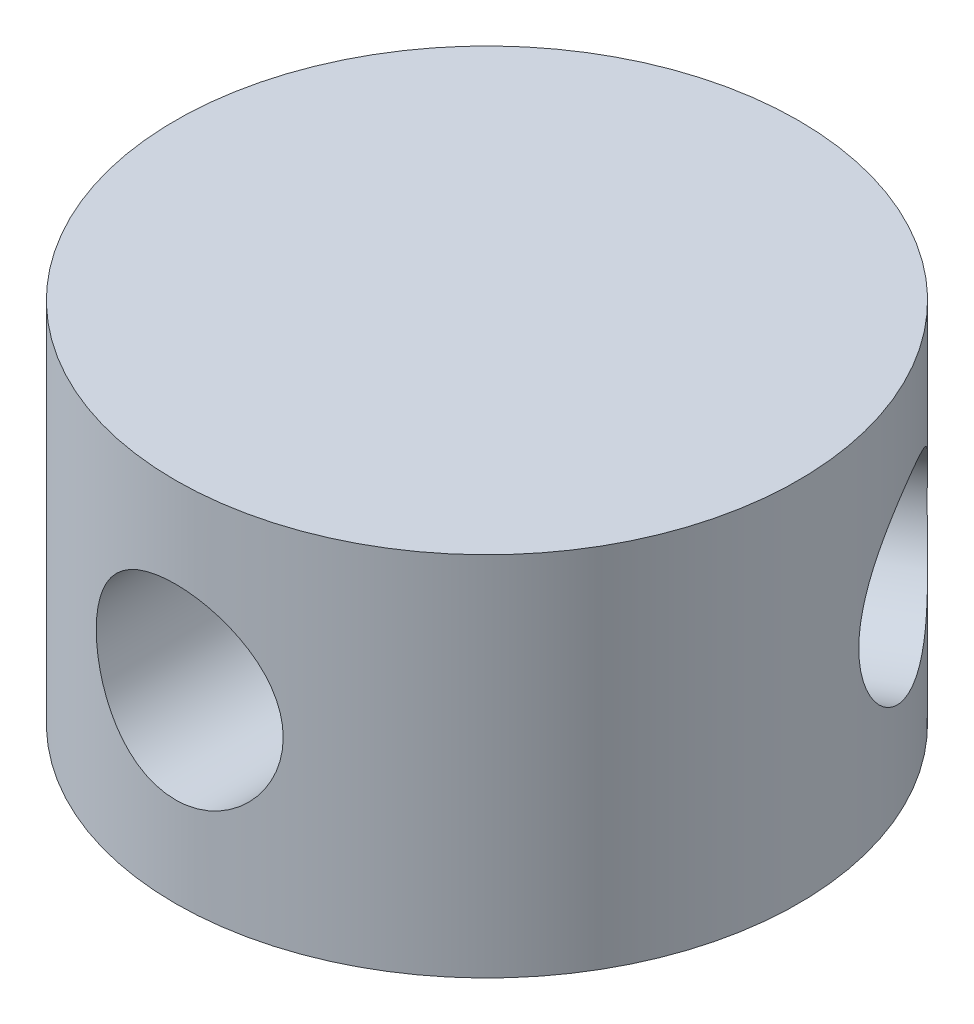
SolidWorks part; units mm, degrees
ref_plane "Front Plane" through (0, 0, 0) normal (0, 0, 1) x (1, 0, 0)
ref_plane "Top Plane" through (0, 0, 0) normal (0, 1, 0) x (1, 0, 0)
ref_plane "Right Plane" through (0, 0, 0) normal (1, 0, 0) x (0, 0, -1)
sketch "cirkel" plane through (0, 0, 0) normal (0, 1, 0) x (1, 0, 0)
  circle A0 centre (0, 0) radius 17
  dimension "D1" = 34
extrude "cilinder" add sketch "cirkel" along normal blind 20
ref_plane "Plane1" through (0, 0, 17) normal (0, 0, 1) x (1, 0, 0)
sketch "cirkel_gat" plane through (0, 0, 17) normal (0, 0, 1) x (1, 0, 0)
  line L0 (-17, 0) -> (17, 0) construction
  line L1 (0, 0) -> (0, 10) construction
  circle A0 centre (0, 10) radius 5.1
  dimension "D1" = 10.2
  dimension "D2" = 10
extrude "opening" cut sketch "cirkel_gat" against normal blind 10 contours A0
pattern_circular "gaten_patroon" count 3 over 360 about axis through (0, 0, 0) along (0, 1, 0) of "opening"
sketch "cirkel1" plane through (0, 0, 0) normal (0, -1, 0) x (-1, 0, 0)
  circle A0 centre (0, 0) radius 13.5
  dimension "D1" = 27
extrude "opening_opzet" cut sketch "cirkel1" against normal blind 3
sketch "cirkel2" plane through (0, 3, 0) normal (0, -1, 0) x (-1, 0, 0)
  circle A0 centre (0, 0) radius 1.9
  dimension "D1" = 3.8
extrude "gat_verloopstuk" cut sketch "cirkel2" against normal blind 8
sketch "cirkel3" plane through (0, 3, 0) normal (0, -1, 0) x (1, 0, 0)
  circle A0 centre (0, 0) radius 2.9
  dimension "D1" = 5.8
extrude "gat_verloopstuk_rand" cut sketch "cirkel3" against normal blind 2
